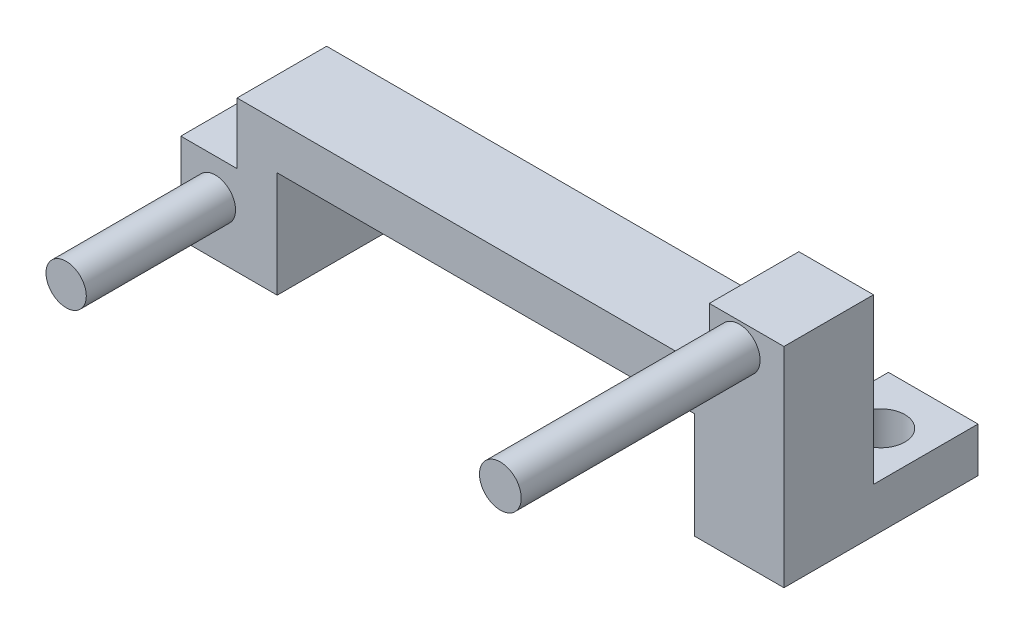
SolidWorks part; units mm, degrees
ref_plane "Front Plane" through (0, 0, 0) normal (0, 0, 1) x (1, 0, 0)
ref_plane "Top Plane" through (0, 0, 0) normal (0, 1, 0) x (1, 0, 0)
ref_plane "Right Plane" through (0, 0, 0) normal (1, 0, 0) x (0, 0, -1)
sketch "Sketch1" plane through (0, 0, 0) normal (0, 0, 1) x (1, 0, 0)
  line L1 (-3.4341, 3.4024) -> (0.5659, 3.4024)
  line L2 (-3.4341, 3.4024) -> (-3.4341, -10.5976)
  line L3 (-3.4341, -10.5976) -> (0.5659, -10.5976)
  line L4 (0.5659, 3.4024) -> (0.5659, -10.5976)
  dimension "D1" = 14
  dimension "D2" = 4
extrude "Boss-Extrude1" add sketch "Sketch1" along normal blind 3
sketch "Sketch2" plane through (0, 0, 0) normal (0, 0, -1) x (-1, 0, 0)
  line L0 (1.4341, -10.5976) -> (1.4341, 1.8024) construction
  line L1 (3.4341, -10.5976) -> (-0.5659, -10.5976) construction
  circle A0 centre (1.4341, 1.8024) radius 1.4
  dimension "D2" = 2.8
  dimension "D1" = 12.4
extrude "Boss-Extrude2" add sketch "Sketch2" along normal blind 16
sketch "Sketch3" plane through (0, 0, 3) normal (0, 0, 1) x (1, 0, 0)
  line L0 (-3.4341, 3.4024) -> (-3.4341, -10.5976) construction
  line L1 (-3.4341, -9.5976) -> (0.5659, -9.5976)
  line L2 (-3.4341, -9.5976) -> (-3.4341, -10.5976)
  line L3 (-3.4341, -10.5976) -> (0.5659, -10.5976)
  line L4 (0.5659, -9.5976) -> (0.5659, -10.5976)
  dimension "D1" = 1
extrude "Boss-Extrude4" add sketch "Sketch3" along normal blind 6
sketch "Sketch7" plane through (-3.4341, 0, 0) normal (-1, 0, 0) x (0, 0, 1)
  line L0 (0, 3.4024) -> (0, -10.5976) construction
  line L1 (0, -1.4976) -> (3, -1.4976)
  line L2 (0, -1.4976) -> (0, -3.4976)
  line L3 (0, -3.4976) -> (3, -3.4976)
  line L4 (3, -1.4976) -> (3, -3.4976)
  line L5 (3, 3.4024) -> (3, -9.5976) construction
  line L6 (9, -10.5976) -> (0, -10.5976) construction
  dimension "D1" = 7.1
  dimension "D2" = 2
extrude "Boss-Extrude5" add sketch "Sketch7" along normal blind 30.95
sketch "Sketch8" plane through (-34.3841, 0, 0) normal (-1, 0, 0) x (0, 0, 1)
  line L1 (0, -1.4976) -> (3, -1.4976)
  line L2 (0, -1.4976) -> (0, -3.4976)
  line L3 (0, -3.4976) -> (3, -3.4976)
  line L4 (3, -1.4976) -> (3, -3.4976)
extrude "Boss-Extrude6" add sketch "Sketch8" along normal blind 1
sketch "Sketch9" plane through (0, 0, 0) normal (0, 0, -1) x (-1, 0, 0)
  line L0 (35.3841, -3.4976) -> (3.4341, -3.4976) construction
  line L1 (35.3841, -1.4976) -> (34.3841, -1.4976)
  line L2 (35.3841, -1.4976) -> (35.3841, -3.4976)
  line L3 (35.3841, -3.4976) -> (34.3841, -3.4976)
  line L4 (34.3841, -1.4976) -> (34.3841, -3.4976)
  dimension "D1" = 1
extrude "Boss-Extrude7" add sketch "Sketch9" along normal blind 3
sketch "Sketch10" plane through (0, 0, -3) normal (0, 0, -1) x (-1, 0, 0)
  line L0 (34.3841, -3.4976) -> (35.3841, -3.4976) construction
  line L1 (34.3841, -1.4976) -> (35.3841, -1.4976)
  line L2 (34.3841, -1.4976) -> (34.3841, -3.4976)
  line L3 (34.3841, -3.4976) -> (35.3841, -3.4976)
  line L4 (35.3841, -1.4976) -> (35.3841, -3.4976)
  line L5 (35.3841, -3.4976) -> (35.3841, -1.4976) construction
extrude "Boss-Extrude8" add sketch "Sketch10" along normal blind 5.92
sketch "Sketch11" plane through (0, 0, -8.92) normal (0, 0, -1) x (-1, 0, 0)
  line L1 (34.3841, -1.4976) -> (35.3841, -1.4976)
  line L2 (34.3841, -1.4976) -> (34.3841, -3.4976)
  line L3 (34.3841, -3.4976) -> (35.3841, -3.4976)
  line L4 (35.3841, -1.4976) -> (35.3841, -3.4976)
extrude "Boss-Extrude9" add sketch "Sketch11" along normal blind 4
sketch "Sketch12" plane through (0, -3.4976, 0) normal (0, -1, 0) x (1, 0, 0)
  line L0 (-35.3841, 3) -> (-35.3841, -7.78) construction
  line L1 (-35.3841, -12.92) -> (-35.3841, 3) construction
  line L2 (-34.3841, -12.92) -> (-34.3841, 0) construction
  line L3 (-35.3841, -7.78) -> (-34.3841, -7.78)
  line L4 (-35.3841, -7.78) -> (-35.3841, -10.78)
  line L5 (-35.3841, -10.78) -> (-34.3841, -10.78)
  line L6 (-34.3841, -7.78) -> (-34.3841, -10.78)
  dimension "D1" = 10.78
  dimension "D2" = 3
extrude "Boss-Extrude14" add sketch "Sketch12" along normal blind 0.93
sketch "Sketch13" plane through (0, -3.4976, 0) normal (0, -1, 0) x (1, 0, 0)
  line L0 (-34.3841, 0) -> (-3.4341, 0) construction
  line L1 (-35.3841, 3) -> (-32.3841, 3)
  line L2 (-35.3841, 3) -> (-35.3841, 0)
  line L3 (-35.3841, 0) -> (-32.3841, 0)
  line L4 (-32.3841, 3) -> (-32.3841, 0)
  dimension "D1" = 3
extrude "Boss-Extrude15" add sketch "Sketch13" along normal blind 7.1
sketch "Sketch14" plane through (0, 0, 3) normal (0, 0, 1) x (1, 0, 0)
  line L0 (-32.3841, -10.5976) -> (-35.3841, -10.5976) construction
  line L1 (-33.6531, -10.5976) -> (-36.9872, -10.5976)
  line L2 (-33.6531, -10.5976) -> (-33.6531, 3.2634)
  line L3 (-33.6531, 3.2634) -> (-36.9872, 3.2634)
  line L4 (-36.9872, -10.5976) -> (-36.9872, 3.2634)
extrude "Cut-Extrude3" cut sketch "Sketch14" against normal blind 10
sketch "Sketch15" plane through (-35.3841, 0, 0) normal (-1, 0, 0) x (0, 0, 1)
  line L1 (-12.92, -1.4976) -> (-6.7133, -1.4976)
  line L2 (-12.92, -1.4976) -> (-12.92, -5.1581)
  line L3 (-12.92, -5.1581) -> (-6.7133, -5.1581)
  line L4 (-6.7133, -1.4976) -> (-6.7133, -5.1581)
extrude "Cut-Extrude4" cut sketch "Sketch15" against normal blind 10
sketch "Sketch16" plane through (-33.6531, 0, 0) normal (-1, 0, 0) x (0, 0, 1)
  line L1 (0, -1.4976) -> (3, -1.4976)
  line L2 (0, -1.4976) -> (0, -10.5976)
  line L3 (0, -10.5976) -> (3, -10.5976)
  line L4 (3, -1.4976) -> (3, -10.5976)
extrude "Boss-Extrude16" add sketch "Sketch16" along normal blind 0.12
sketch "Sketch18" plane through (-33.7731, 0, 0) normal (-1, 0, 0) x (0, 0, 1)
  line L1 (0, -1.4976) -> (3, -1.4976)
  line L2 (0, -1.4976) -> (0, -10.5976)
  line L3 (0, -10.5976) -> (3, -10.5976)
  line L4 (3, -1.4976) -> (3, -10.5976)
extrude "Boss-Extrude18" add sketch "Sketch18" along normal blind 0.41
sketch "Sketch19" plane through (-34.1831, 0, 0) normal (-1, 0, 0) x (0, 0, 1)
  line L1 (0, -1.4976) -> (3, -1.4976)
  line L2 (0, -1.4976) -> (0, -10.5976)
  line L3 (0, -10.5976) -> (3, -10.5976)
  line L4 (3, -1.4976) -> (3, -10.5976)
extrude "Boss-Extrude19" add sketch "Sketch19" along normal blind 0.89
sketch "Sketch20" plane through (-35.0731, 0, 0) normal (-1, 0, 0) x (0, 0, 1)
  line L0 (0, -1.4976) -> (0, -10.5976) construction
  line L1 (0, -4.5976) -> (3, -4.5976)
  line L2 (0, -4.5976) -> (0, -10.5976)
  line L3 (0, -10.5976) -> (3, -10.5976)
  line L4 (3, -4.5976) -> (3, -10.5976)
  line L5 (9, -10.5976) -> (0, -10.5976) construction
  line L6 (3, -10.5976) -> (3, -1.4976) construction
  dimension "D1" = 3.1
extrude "Boss-Extrude20" add sketch "Sketch20" along normal blind 3.77
sketch "Sketch21" plane through (0, 0, 0) normal (0, 0, -1) x (-1, 0, 0)
  line L0 (35.0731, -4.5976) -> (35.0731, -5.5976) construction
  line L1 (35.0731, -5.5976) -> (36.5231, -5.5976) construction
  line L2 (36.5231, -5.5976) -> (36.5231, -7.0476) construction
  circle A0 centre (36.5231, -7.0476) radius 1.35
  dimension "D4" = 2.7
  dimension "D1" = 1
  dimension "D2" = 1.45
  dimension "D3" = 1.45
extrude "Boss-Extrude23" add sketch "Sketch21" along normal blind 10
sketch "Sketch23" plane through (0, 0, 3) normal (0, 0, 1) x (1, 0, 0)
  line L0 (-38.8431, -10.5976) -> (-38.8431, -4.5976)
  line L1 (-38.8431, -4.5976) -> (-35.0731, -4.5976)
  line L2 (-35.0731, -4.5976) -> (-35.0731, -1.4976)
  line L3 (-35.0731, -1.4976) -> (-3.4341, -1.4976)
  line L4 (-3.4341, -1.4976) -> (-3.4341, 3.4024)
  line L5 (-3.4341, 3.4024) -> (0.5659, 3.4024)
  line L6 (0.5659, 3.4024) -> (0.5659, -9.5976)
  line L7 (0.5659, -9.5976) -> (-3.4341, -9.5976)
  line L8 (-3.4341, -9.5976) -> (-3.4341, -3.4976)
  line L9 (-3.4341, -3.4976) -> (-32.3841, -3.4976)
  line L10 (-32.3841, -3.4976) -> (-32.3841, -10.5976)
  line L11 (-32.3841, -10.5976) -> (-38.8431, -10.5976)
extrude "Boss-Extrude24" add sketch "Sketch23" along normal blind 3
sketch "Sketch24" plane through (0, 0, 9) normal (0, 0, 1) x (1, 0, 0)
  line L1 (-3.4341, -9.5976) -> (0.5659, -9.5976)
  line L2 (-3.4341, -9.5976) -> (-3.4341, -10.5976)
  line L3 (-3.4341, -10.5976) -> (0.5659, -10.5976)
  line L4 (0.5659, -9.5976) -> (0.5659, -10.5976)
extrude "Boss-Extrude25" add sketch "Sketch24" along normal blind 4
sketch "Sketch25" plane through (0, -9.5976, 0) normal (0, 1, 0) x (1, 0, 0)
  line L1 (-3.4341, -6) -> (0.5659, -6)
  line L2 (-3.4341, -6) -> (-3.4341, -13)
  line L3 (-3.4341, -13) -> (0.5659, -13)
  line L4 (0.5659, -6) -> (0.5659, -13)
extrude "Boss-Extrude26" add sketch "Sketch25" along normal blind 2
sketch "Sketch26" plane through (0, 0, 6) normal (0, 0, 1) x (1, 0, 0)
  line L0 (-38.8431, -4.5976) -> (-38.8431, -10.5976) construction
  line L1 (-32.3841, -10.5976) -> (-38.8431, -10.5976)
  line L2 (-32.3841, -10.5976) -> (-32.3841, -7.5976)
  line L3 (-32.3841, -7.5976) -> (-38.8431, -7.5976)
  line L4 (-38.8431, -10.5976) -> (-38.8431, -7.5976)
  dimension "D1" = 3
extrude "Boss-Extrude27" add sketch "Sketch26" along normal blind 7
sketch "Sketch27" plane through (0, -7.5976, 0) normal (0, 1, 0) x (1, 0, 0)
  line L0 (-38.8431, -9.5) -> (-32.3841, -9.5) construction
  line L1 (-38.8431, -13) -> (-38.8431, -6) construction
  line L2 (-32.3841, -13) -> (-32.3841, -6) construction
  line L3 (-35.6136, -13) -> (-35.6136, -6) construction
  line L4 (-32.3841, -13) -> (-38.8431, -13) construction
  line L5 (-32.3841, -6) -> (-38.8431, -6) construction
  circle A0 centre (-35.6136, -9.5) radius 1.6
  dimension "D1" = 3.2
extrude "Cut-Extrude5" cut sketch "Sketch27" against normal blind 7
sketch "Sketch28" plane through (0, -7.5976, 0) normal (0, 1, 0) x (1, 0, 0)
  line L0 (-1.4341, -13) -> (-1.4341, -6) construction
  line L1 (-3.4341, -13) -> (0.5659, -13) construction
  line L2 (0.5659, -6) -> (-3.4341, -6) construction
  line L3 (-3.4341, -9.5) -> (0.5659, -9.5) construction
  line L4 (-3.4341, -6) -> (-3.4341, -13) construction
  line L5 (0.5659, -13) -> (0.5659, -6) construction
  circle A0 centre (-1.4341, -9.5) radius 1.6
  dimension "D1" = 3.2
extrude "Cut-Extrude6" cut sketch "Sketch28" against normal blind 7
sketch "Sketch31" plane through (-3.4341, 0, 0) normal (-1, 0, 0) x (0, 0, 1)
  line L1 (6, -7.5976) -> (13, -7.5976)
  line L2 (6, -7.5976) -> (6, -10.5976)
  line L3 (6, -10.5976) -> (13, -10.5976)
  line L4 (13, -7.5976) -> (13, -10.5976)
extrude "Boss-Extrude30" add sketch "Sketch31" along normal blind 1
sketch "Sketch32" plane through (-3.4341, 0, 0) normal (-1, 0, 0) x (0, 0, 1)
  line L1 (0, -3.4976) -> (6, -3.4976)
  line L2 (0, -3.4976) -> (0, -10.5976)
  line L3 (0, -10.5976) -> (6, -10.5976)
  line L4 (6, -3.4976) -> (6, -10.5976)
extrude "Boss-Extrude31" add sketch "Sketch32" along normal blind 1
sketch "Sketch33" plane through (0, -1.4976, 0) normal (0, 1, 0) x (1, 0, 0)
  line L0 (-3.4341, -6) -> (-3.4341, 0) construction
  line L1 (-35.0731, 0) -> (-3.4341, 0)
  line L2 (-35.0731, 0) -> (-35.0731, -6)
  line L3 (-35.0731, -6) -> (-3.4341, -6)
  line L4 (-3.4341, 0) -> (-3.4341, -6)
  line L5 (-3.4341, -6) -> (-35.0731, -6) construction
extrude "Boss-Extrude32" add sketch "Sketch33" along normal blind 1
mirror "Mirror1" about plane through (0, 0, 13) normal (0, 0, 1) of bodies 138 139
delete or keep bodies "Body-Delete/Keep 1" type delete bodies bodies 138
sketch "Sketch34" plane through (0.5659, 0, 0) normal (1, 0, 0) x (0, 0, -1)
  line L0 (-26, 3.4024) -> (-20, 3.4024)
  line L1 (-20, 3.4024) -> (-20, -7.5976)
  line L2 (-20, -7.5976) -> (-13, -7.5976)
  line L3 (-13, -7.5976) -> (-13, -10.5976)
  line L4 (-13, -10.5976) -> (-26, -10.5976)
  line L5 (-26, -10.5976) -> (-26, 3.4024)
extrude "Boss-Extrude33" add sketch "Sketch34" along normal blind 1
